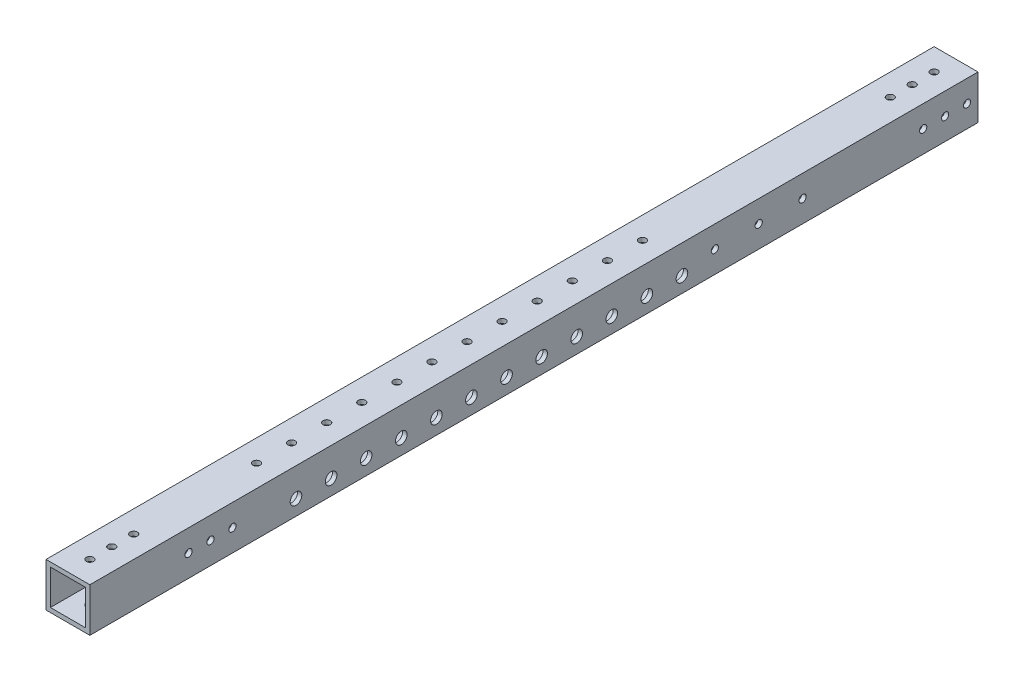
SolidWorks part; units mm, degrees
ref_plane "前视基准面" through (0, 0, 0) normal (0, 0, 1) x (1, 0, 0)
ref_plane "上视基准面" through (0, 0, 0) normal (0, 1, 0) x (1, 0, 0)
ref_plane "右视基准面" through (0, 0, 0) normal (1, 0, 0) x (0, 0, -1)
other "Configuration Table"
sketch "草图1" plane through (0, 0, 0) normal (0, 0, 1) x (1, 0, 0)
  line L1 (-8, -8) -> (8, -8)
  line L2 (-8, -8) -> (-8, 8)
  line L3 (-8, 8) -> (8, 8)
  line L4 (8, -8) -> (8, 8)
  line L5 (-8, -8) -> (8, 8) construction
  line L6 (-8, 8) -> (8, -8) construction
  line L7 (-10, -10) -> (10, -10)
  line L8 (-10, -10) -> (-10, 10)
  line L9 (-10, 10) -> (10, 10)
  line L10 (10, -10) -> (10, 10)
  line L11 (-10, -10) -> (10, 10) construction
  line L12 (-10, 10) -> (10, -10) construction
  point P0 (0, 0)
  point P6 (0, 0)
  dimension "D1" = 20
  dimension "D2" = 20
  dimension "D3" = 2
  dimension "D4" = 2
extrude "凸台-拉伸1" add sketch "草图1" along normal blind 405
sketch "草图2" plane through (0, 0, 0) normal (0, 1, 0) x (1, 0, 0)
  line L0 (0, 0) -> (0, -405) construction
  line L1 (10, -405) -> (-10, -405) construction
  circle A0 centre (0, -395) radius 1.65
  circle A1 centre (0, -385) radius 1.65
  circle A2 centre (0, -375) radius 1.65
  dimension "D1" = 3.3
  dimension "D3" = 3.3
  dimension "D4" = 3.3
  dimension "D2" = 10
  dimension "D5" = 10
  dimension "D6" = 10
extrude "切除-拉伸1" cut sketch "草图2" against normal mid plane 20
sketch "草图4" plane through (0, 0, 0) normal (0, 1, 0) x (1, 0, 0)
  line L0 (-10, -10) -> (10, -10) construction
  line L1 (-10, -405) -> (-10, 0) construction
  line L2 (10, -405) -> (10, 0) construction
  line L3 (10, 0) -> (-10, 0) construction
  circle A0 centre (0, -10) radius 1.65
  circle A1 centre (0, -20) radius 1.65
  circle A2 centre (0, -30) radius 1.65
  dimension "D2" = 3.3
  dimension "D3" = 3.3
  dimension "D4" = 3.3
  dimension "D1" = 10
  dimension "D5" = 10
  dimension "D6" = 20
extrude "切除-拉伸3" cut sketch "草图4" against normal mid plane 20
sketch "草图10" plane through (10, 0, 0) normal (1, 0, 0) x (0, 0, -1)
  line L0 (0, -10) -> (0, 10) construction
  line L1 (-135, -3) -> (-327, -3) construction
  line L2 (-405, 10) -> (0, 10) construction
  circle A0 centre (-120, 0) radius 1.65
  circle A1 centre (-100, 0) radius 1.65
  circle A2 centre (-80, 0) radius 1.65
  circle A3 centre (-135, -3) radius 2.65
  circle A4 centre (-151, -3) radius 2.65
  circle A5 centre (-167, -3) radius 2.65
  circle A6 centre (-183, -3) radius 2.65
  circle A7 centre (-199, -3) radius 2.65
  circle A8 centre (-215, -3) radius 2.65
  circle A9 centre (-231, -3) radius 2.65
  circle A10 centre (-247, -3) radius 2.65
  circle A11 centre (-263, -3) radius 2.65
  circle A12 centre (-279, -3) radius 2.65
  circle A13 centre (-295, -3) radius 2.65
  circle A14 centre (-311, -3) radius 2.65
  circle A17 centre (-327, -3) radius 2.65 [skipped]
  circle A18 centre (-360, 0) radius 1.65
  circle A19 centre (-350, 0) radius 1.65
  circle A20 centre (-340, 0) radius 1.65
  circle A24 centre (-5, 0) radius 1.65
  circle A25 centre (-15, 0) radius 1.65
  circle A26 centre (-25, 0) radius 1.65
  dimension "D1" = 3.3
  dimension "D3" = 3.3
  dimension "D4" = 3.3
  dimension "D7" = 5.3
  dimension "D12" = 3.3
  dimension "D18" = 5
  dimension "D19" = 10
  dimension "D20" = 10
  dimension "D15" = 3.3
  dimension "D16" = 3.3
  dimension "D17" = 3.3
  dimension "D2" = 120
  dimension "D5" = 20
  dimension "D6" = 20
  dimension "D8" = 15
  dimension "D10" = 13
  dimension "D11" = 360
  dimension "D13" = 10
  dimension "D9" = 13
  dimension "D14" = 3
extrude "切除-拉伸4" cut sketch "草图10" against normal through all
sketch "草图11" plane through (0, 10, 0) normal (0, 1, 0) x (1, 0, 0)
  line L0 (0, 0) -> (0, -143) construction
  circle A0 centre (0, -143) radius 1.65
  circle A1 centre (0, -159) radius 1.65
  circle A2 centre (0, -175) radius 1.65
  circle A3 centre (0, -191) radius 1.65
  circle A4 centre (0, -207) radius 1.65
  circle A5 centre (0, -223) radius 1.65
  circle A6 centre (0, -239) radius 1.65
  circle A7 centre (0, -255) radius 1.65
  circle A8 centre (0, -271) radius 1.65
  circle A9 centre (0, -287) radius 1.65
  circle A10 centre (0, -303) radius 1.65
  circle A11 centre (0, -319) radius 1.65
  dimension "D2" = 3.3
  dimension "D1" = 143
  dimension "D3" = 12
extrude "切除-拉伸5" cut sketch "草图11" against normal through all
